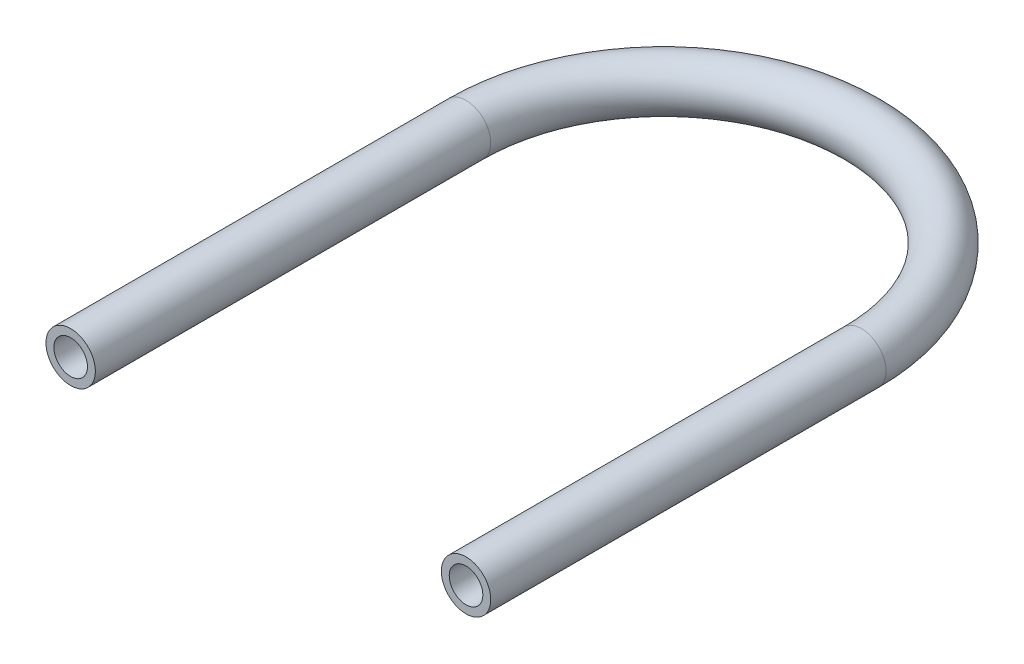
SolidWorks part; units mm, degrees
material "Copper"
ref_plane "Front Plane" through (0, 0, 0) normal (0, 0, 1) x (1, 0, 0)
ref_plane "Top Plane" through (0, 0, 0) normal (0, 1, 0) x (1, 0, 0)
ref_plane "Right Plane" through (0, 0, 0) normal (1, 0, 0) x (0, 0, -1)
sketch "Sketch3" plane through (0, 0, 0) normal (0, 1, 0) x (1, 0, 0)
  line L0 (-25.4, 0) -> (-25.4, 50.8)
  line L1 (25.4, 0) -> (25.4, 50.8)
  arc A0 (-25.4, 50.8) -> (25.4, 50.8) centre (0, 50.8) cw
  dimension "D4" = 25.4
  dimension "D1" = 50.8
  dimension "D2" = 25.4
  dimension "D3" = 50.8
sketch "Sketch4" plane through (0, 0, 0) normal (0, 0, 1) x (1, 0, 0)
  circle A0 centre (-25.4, 0) radius 3.175
  circle A1 centre (-25.4, 0) radius 2.159
  dimension "D1" = 6.35
  dimension "D2" = 4.318
sweep "Sweep1" add profiles "Sketch4" path "Sketch3"
